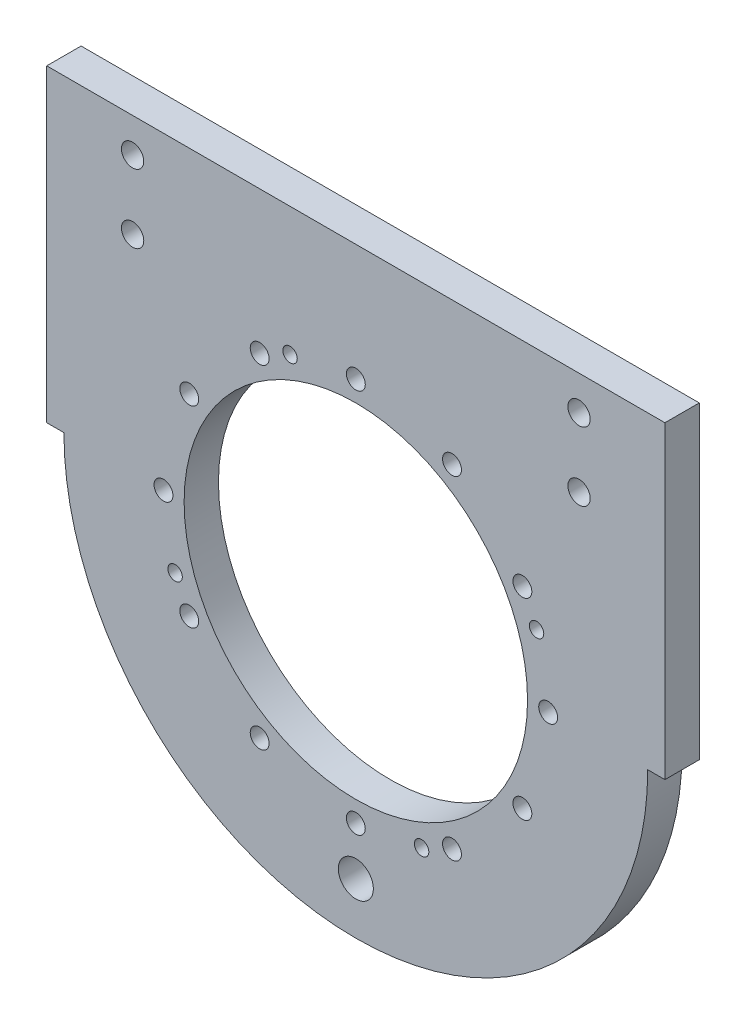
SolidWorks part; units mm, degrees
material "6061-T6 (SS)"
ref_plane "前视基准面" through (0, 0, 0) normal (0, 0, 1) x (1, 0, 0)
ref_plane "上视基准面" through (0, 0, 0) normal (0, 1, 0) x (1, 0, 0)
ref_plane "右视基准面" through (0, 0, 0) normal (1, 0, 0) x (0, 0, -1)
other "Configuration Table"
sketch "草图1" plane through (0, 0, 0) normal (0, 0, 1) x (1, 0, 0)
  circle A0 centre (0, 0) radius 85
extrude "凸台-拉伸1" add sketch "草图1" along normal blind 10
sketch "草图2" plane through (0, 0, 0) normal (0, 0, 1) x (1, 0, 0)
  line L0 (-90, 0) -> (90, 0)
  line L1 (90, 0) -> (90, 90)
  line L2 (90, 90) -> (-90, 90)
  line L3 (-90, 90) -> (-90, 0)
extrude "凸台-拉伸2" add sketch "草图2" along normal blind 10
sketch "草图3" plane through (0, 0, 0) normal (0, 0, -1) x (-1, 0, 0)
  circle A0 centre (0, 0) radius 50
  circle A1 centre (-56, 0) radius 2.75
  circle A2 centre (-48.4974, 28) radius 2.75
  circle A3 centre (-28, 48.4974) radius 2.75
  circle A4 centre (0, 56) radius 2.75
  circle A5 centre (28, 48.4974) radius 2.75
  circle A6 centre (48.4974, 28) radius 2.75
  circle A7 centre (56, 0) radius 2.75
  circle A8 centre (48.4974, -28) radius 2.75
  circle A9 centre (28, -48.4974) radius 2.75
  circle A10 centre (0, -56) radius 2.75
  circle A11 centre (-28, -48.4974) radius 2.75
  circle A12 centre (-48.4974, -28) radius 2.75
  circle A13 centre (-52.6228, 19.1531) radius 2.1
  circle A14 centre (19.1531, 52.6228) radius 2.1
  circle A15 centre (52.6228, -19.1531) radius 2.1
  circle A16 centre (-19.1531, -52.6228) radius 2.1
  circle A17 centre (0, -70) radius 5.1
  circle A18 centre (65, 60) radius 3.25
  circle A19 centre (65, 80) radius 3.25
  circle A20 centre (-65, 60) radius 3.25
  circle A21 centre (-65, 80) radius 3.25
extrude "切除-拉伸1" cut sketch "草图3" against normal blind 11
